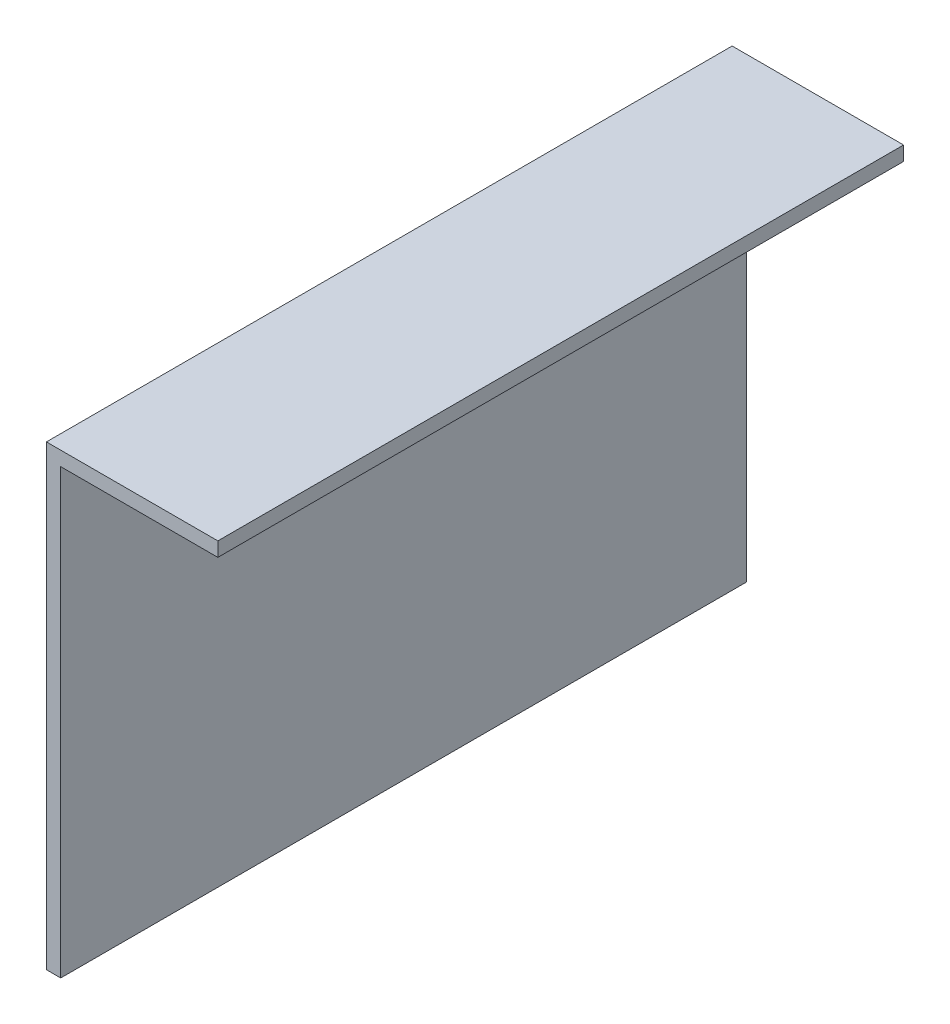
SolidWorks part; units mm, degrees
ref_plane "Front Plane" through (0, 0, 0) normal (0, 0, 1) x (1, 0, 0)
ref_plane "Top Plane" through (0, 0, 0) normal (0, 1, 0) x (1, 0, 0)
ref_plane "Right Plane" through (0, 0, 0) normal (1, 0, 0) x (0, 0, -1)
sketch "Sketch1" plane through (0, 0, 0) normal (0, 0, 1) x (1, 0, 0)
  line L0 (1.5875, 47.625) -> (36.5125, 47.625)
  line L1 (1.5875, -50.8) -> (-1.5875, -50.8)
  line L2 (1.5875, -50.8) -> (1.5875, 47.625)
  line L4 (-1.5875, -50.8) -> (-1.5875, 50.8)
  line L5 (1.5875, -50.8) -> (-1.5875, 50.8) construction
  line L6 (3.5127, 112.4075) -> (-1.5875, -50.8) construction
  line L7 (-1.5875, 50.8) -> (36.5125, 50.8)
  line L10 (36.5125, 50.8) -> (36.5125, 47.625)
  point P0 (0, 0)
  point P7 (0, -50.8)
  dimension "D1" = 3.175
  dimension "D2" = 3.175
  dimension "D3" = 38.1
  dimension "D4" = 101.6
extrude "Boss-Extrude1" add sketch "Sketch1" along normal blind 152.4
equation "\"eighthinch\"= 0.125"
equation "\"D2@Sketch1\"=\"eighthinch\""
